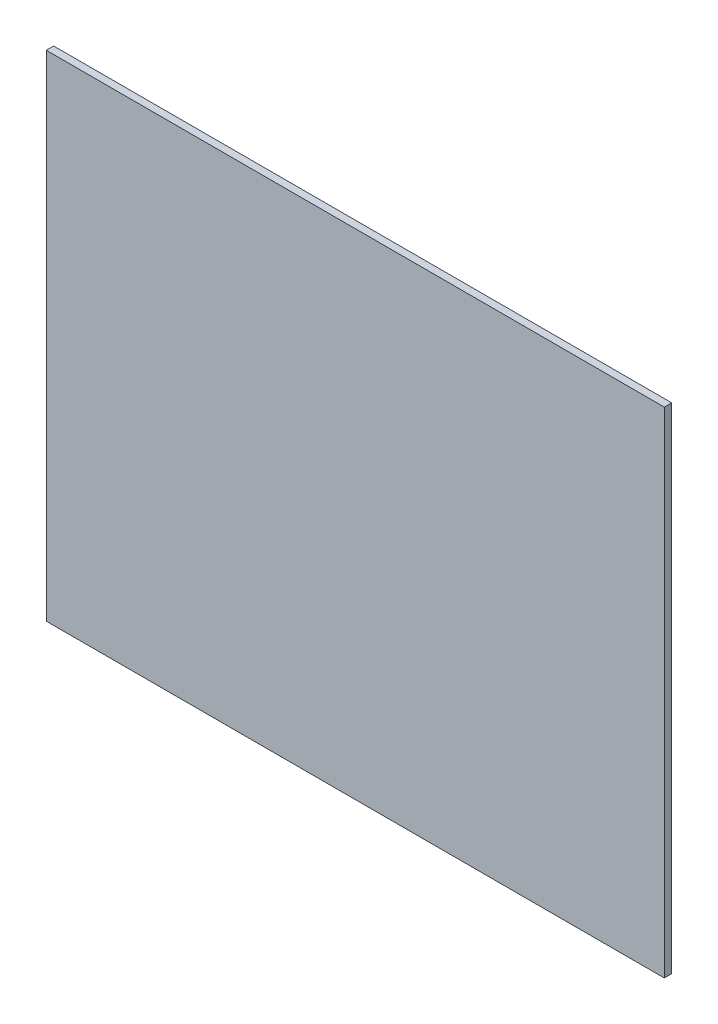
SolidWorks part; units mm, degrees
ref_plane "Front Plane" through (0, 0, 0) normal (0, 0, 1) x (1, 0, 0)
ref_plane "Top Plane" through (0, 0, 0) normal (0, 1, 0) x (1, 0, 0)
ref_plane "Right Plane" through (0, 0, 0) normal (1, 0, 0) x (0, 0, -1)
sketch "Sketch1" plane through (0, 0, 0) normal (0, 0, 1) x (1, 0, 0)
  line L1 (-125, -100) -> (125, -100)
  line L2 (-125, -100) -> (-125, 100)
  line L3 (-125, 100) -> (125, 100)
  line L4 (125, -100) -> (125, 100)
  line L5 (-125, -100) -> (125, 100) construction
  line L6 (-125, 100) -> (125, -100) construction
  point P0 (0, 0)
  dimension "D1" = 200
  dimension "D2" = 250
extrude "Boss-Extrude1" add sketch "Sketch1" along normal blind 3
